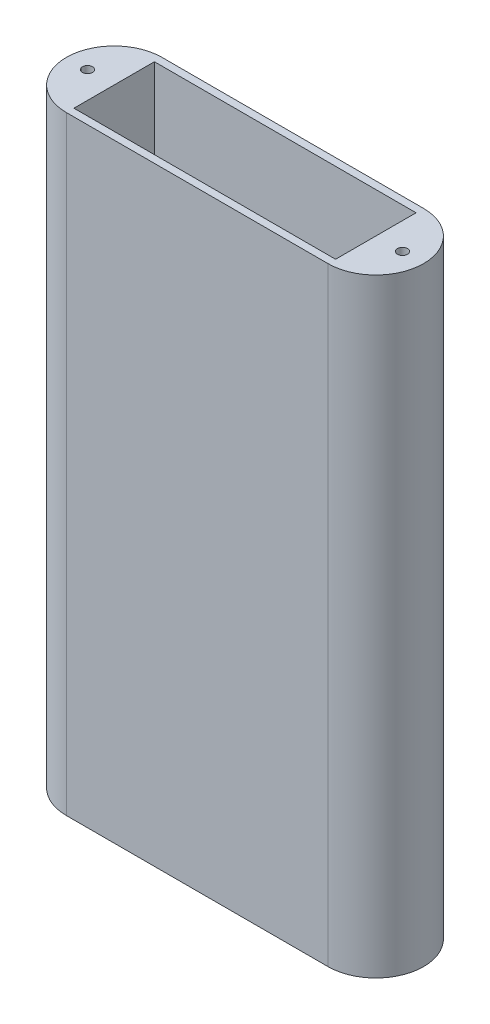
SolidWorks part; units mm, degrees
ref_plane "Front Plane" through (0, 0, 0) normal (0, 0, 1) x (1, 0, 0)
ref_plane "Top Plane" through (0, 0, 0) normal (0, 1, 0) x (1, 0, 0)
ref_plane "Right Plane" through (0, 0, 0) normal (1, 0, 0) x (0, 0, -1)
sketch "Sketch1" plane through (0, 0, 0) normal (0, 1, 0) x (1, 0, 0)
  line L0 (-26, 0) -> (26, 0) construction
  line L1 (-26, 9.5) -> (26, 9.5)
  line L2 (-26, -9.5) -> (26, -9.5)
  arc A0 (-26, 9.5) -> (-26, -9.5) centre (-26, 0) ccw
  arc A1 (26, -9.5) -> (26, 9.5) centre (26, 0) ccw
  point P2 (0, 0)
  point P8 (-35.5, 0)
  point P9 (35.5, 0)
  dimension "D1" = 71
  dimension "D2" = 19
extrude "Boss-Extrude1" add sketch "Sketch1" along normal mid plane 121
shell "Shell1" thickness 1.5
sketch "Sketch2" plane through (0, 0, 0) normal (0, 1, 0) x (1, 0, 0)
  line L0 (-26, -8) -> (-26, 8)
  line L1 (-26, 0) -> (-34, 0) construction
  arc A0 (-26, 8) -> (-26, -8) centre (-26, 0) ccw construction
  arc A1 (-26, 8) -> (-26, -8) centre (-26, 0) ccw
  circle A2 centre (-31.3, 0) radius 1
  arc A3 (-26, 9.5) -> (-26, -9.5) centre (-26, 0) ccw construction
  point P8 (-35.5, 0)
  dimension "D1" = 2
  dimension "D2" = 4.2
extrude "Boss-Extrude2" add sketch "Sketch2" along normal mid plane 121 contours L1 L0 A1 A2 | L0 L1 A2 A1
mirror "Mirror1" about plane through (0, 0, 0) normal (1, 0, 0) of "Boss-Extrude2"
